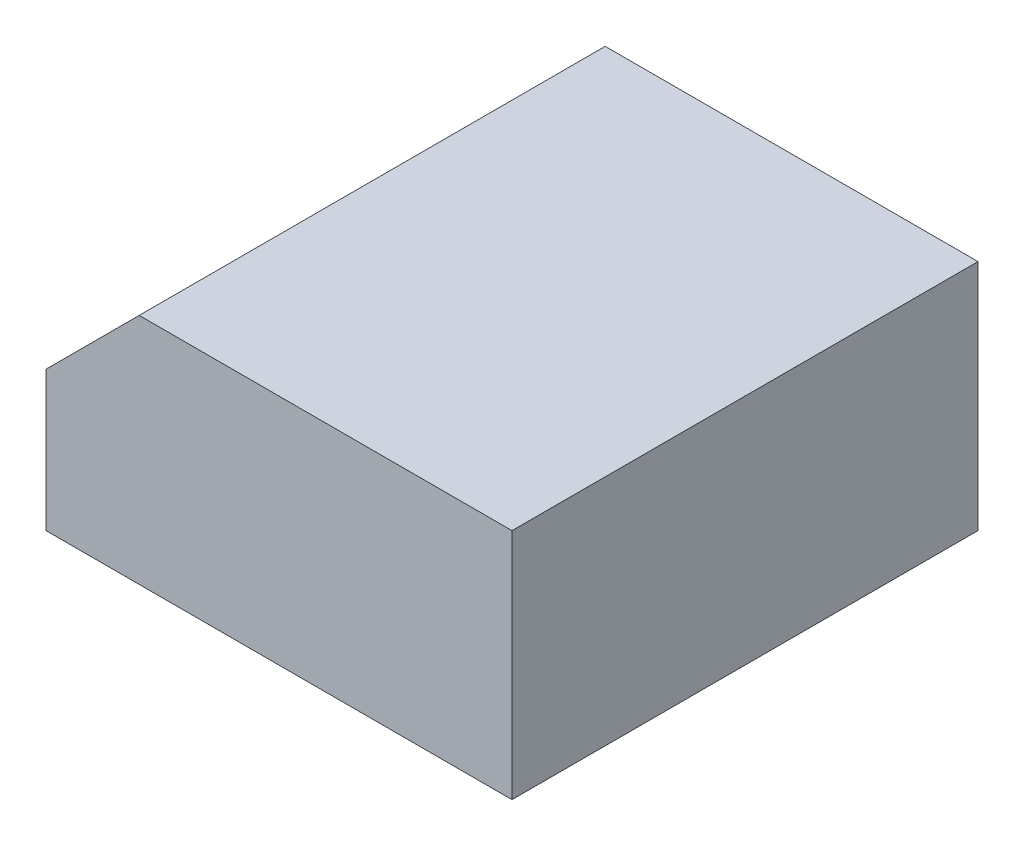
SolidWorks part; units mm, degrees
ref_plane "Front Plane" through (0, 0, 0) normal (0, 0, 1) x (1, 0, 0)
ref_plane "Top Plane" through (0, 0, 0) normal (0, 1, 0) x (1, 0, 0)
ref_plane "Right Plane" through (0, 0, 0) normal (1, 0, 0) x (0, 0, -1)
sketch "Sketch1" plane through (0, 0, 0) normal (0, 0, 1) x (1, 0, 0)
  line L0 (-500, 0) -> (500, 0)
  line L1 (-500, 0) -> (-500, 300)
  line L2 (-500, 300) -> (-300, 500)
  line L3 (-300, 500) -> (500, 500)
  line L4 (500, 500) -> (500, 0)
  dimension "D1" = 1000
  dimension "D2" = 500
  dimension "D3" = 45
  dimension "D4" = 800
extrude "Boss-Extrude1" add sketch "Sketch1" along normal mid plane 1000
sketch "Sketch2" plane through (0, 500, 0) normal (0, 1, 0) x (1, 0, 0)
  line L1 (-275, 475) -> (475, 475)
  line L2 (-275, 475) -> (-275, -475)
  line L3 (-275, -475) -> (475, -475)
  line L4 (475, 475) -> (475, -475)
  line L6 (500, 500) -> (-300, 500) construction
  line L7 (500, -500) -> (500, 500) construction
  dimension "D1" = 750
  dimension "D2" = 950
  dimension "D3" = 25
  dimension "D4" = 25
extrude "Cut-Extrude1" cut sketch "Sketch2" against normal blind 480
sketch "Sketch3" plane through (0, 500, 0) normal (0, 1, 0) x (1, 0, 0)
  line L1 (-275, 475) -> (475, 475)
  line L2 (-275, 475) -> (-275, -475)
  line L3 (-275, -475) -> (475, -475)
  line L4 (475, 475) -> (475, -475)
extrude "Boss-Extrude2" add sketch "Sketch3" against normal blind 10
